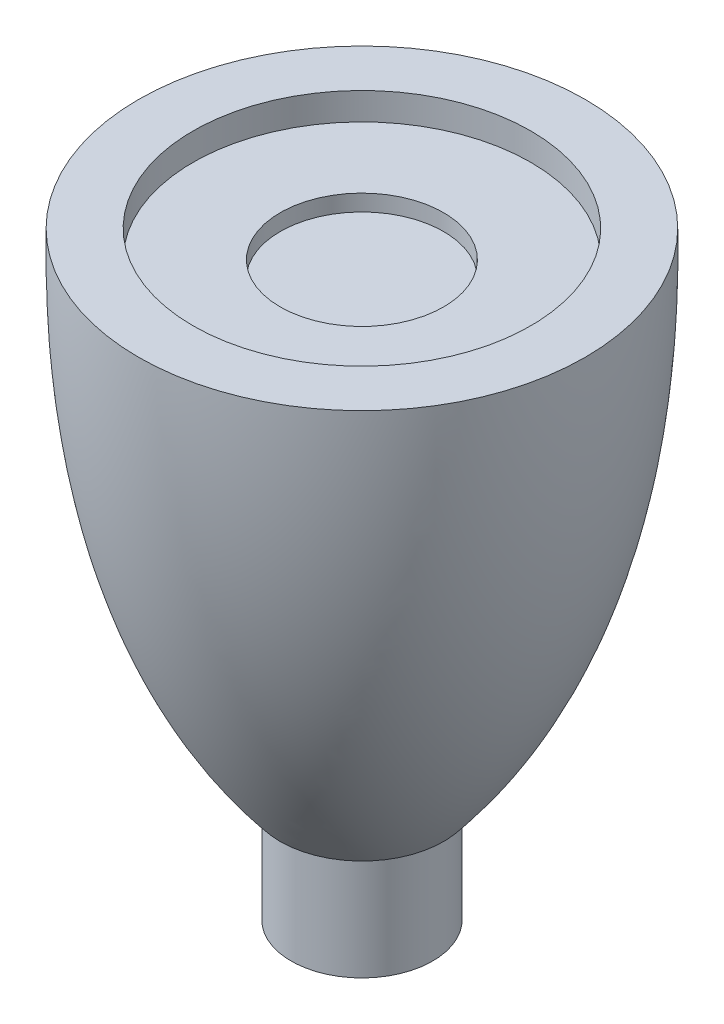
SolidWorks part; units mm, degrees
ref_plane "Front Plane" through (0, 0, 0) normal (0, 0, 1) x (1, 0, 0)
ref_plane "Top Plane" through (0, 0, 0) normal (0, 1, 0) x (1, 0, 0)
ref_plane "Right Plane" through (0, 0, 0) normal (1, 0, 0) x (0, 0, -1)
sketch "Sketch1" plane through (0, 0, 0) normal (0, 0, 1) x (1, 0, 0)
  line L0 (0, 45) -> (0, 0)
  line L1 (0, 45) -> (-20.5, 45) construction
  line L2 (0, 45) -> (0, 0) construction
  line L6 (-7.5, 0) -> (0, 0)
  line L7 (-20.5, 45) -> (0, 45)
  spline S1 degree 2 poles (-20.5, 45) (-20.9455, 16.4461) (-7.5, 0) knots 0 0 0 0.557032 0.557032 0.557032
  dimension "D2" = 7.5
  dimension "D3" = 20.5
revolve "Revolve1" add sketch "Sketch1" angle 360 about L0
sketch "Sketch2" plane through (0, 45, 0) normal (0, 1, 0) x (1, 0, 0)
  circle A0 centre (0, 0) radius 15.5
  dimension "D1" = 31
extrude "Cut-Extrude1" cut sketch "Sketch2" against normal blind 2.5
sketch "Sketch3" plane through (0, 45, 0) normal (0, 1, 0) x (1, 0, 0)
  circle A0 centre (0, 0) radius 7.5
  dimension "D1" = 15
extrude "Cut-Extrude2" cut sketch "Sketch3" against normal blind 4
sketch "Sketch4" plane through (0, 0, 0) normal (0, -1, 0) x (1, 0, 0)
  circle A0 centre (0, 0) radius 6.5
  dimension "D1" = 13
extrude "Boss-Extrude1" add sketch "Sketch4" along normal blind 10
sketch "Sketch6" plane through (0, 0, 0) normal (0, 0, 1) x (1, 0, 0)
  line L0 (0, 36) -> (0, 0)
  line L2 (0, 36) -> (0, 0) construction
  line L6 (0, 36) -> (-15.2753, 36)
  line L7 (-6.5, -10) -> (6.5, -10) construction
  line L9 (-2.5, 0) -> (-2.5, -10)
  line L10 (-2.5, -10) -> (0, -10)
  line L11 (0, 0) -> (0, -10)
  spline S0 degree 3 poles (-15.2753, 36) (-14.2588, 21.1742) (-10.0004, 9.1742) (-2.5, 0) knots 0.090934 0.090934 0.090934 0.090934 0.557032 0.557032 0.557032 0.557032
  dimension "D2" = 2.5
revolve "Cut-Revolve1" cut sketch "Sketch6" angle 360 about L2
